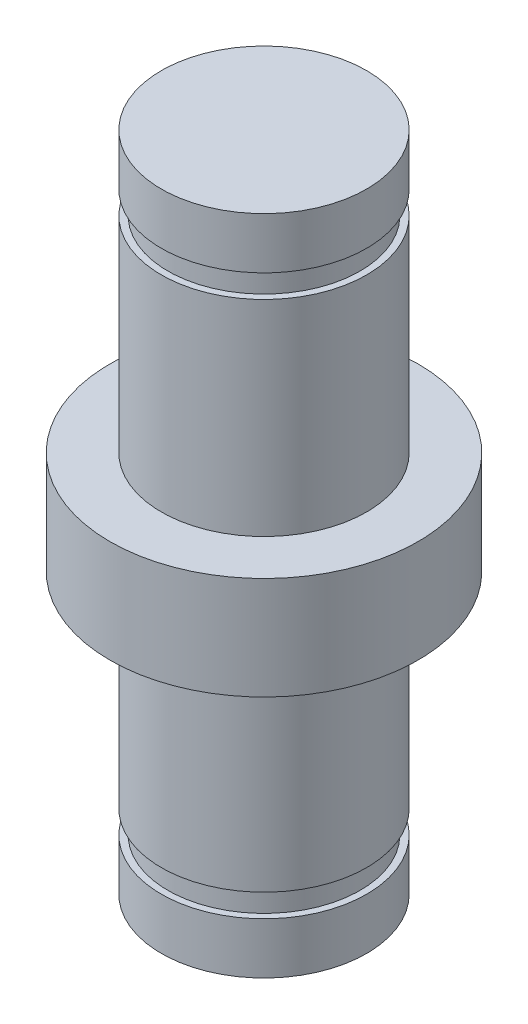
SolidWorks part; units mm, degrees
material "6061 Alloy"
ref_plane "Front Plane" through (0, 0, 0) normal (0, 0, 1) x (1, 0, 0)
ref_plane "Top Plane" through (0, 0, 0) normal (0, 1, 0) x (1, 0, 0)
ref_plane "Right Plane" through (0, 0, 0) normal (1, 0, 0) x (0, 0, -1)
sketch "Sketch1" plane through (0, 0, 0) normal (0, 0, 1) x (1, 0, 0)
  line L0 (0, 0) -> (0, 40.9448) construction
  line L1 (0, 40.9448) -> (6.35, 40.9448)
  line L2 (6.35, 40.9448) -> (6.35, 37.7698)
  line L3 (6.35, 0) -> (0, 0)
  line L4 (0, 0) -> (0, 40.9448) construction
  line L5 (6.35, 37.7698) -> (5.9436, 37.7698)
  line L6 (5.9436, 37.7698) -> (5.9436, 36.3474)
  line L7 (5.9436, 36.3474) -> (6.35, 36.3474)
  line L8 (6.35, 36.3474) -> (6.35, 23.6474)
  line L9 (6.35, 23.6474) -> (9.525, 23.6474)
  line L10 (9.525, 23.6474) -> (9.525, 17.2974)
  line L11 (9.525, 17.2974) -> (6.35, 17.2974)
  line L12 (6.35, 17.2974) -> (6.35, 4.5974)
  line L13 (6.35, 4.5974) -> (5.9436, 4.5974)
  line L14 (5.9436, 4.5974) -> (5.9436, 3.175)
  line L15 (5.9436, 3.175) -> (6.35, 3.175)
  line L16 (6.35, 3.175) -> (6.35, 0)
  line L17 (0, 0) -> (0, 40.9448)
  dimension "D1" = 12.7
  dimension "D2" = 1.4224
  dimension "D3" = 12.7
  dimension "D4" = 11.8872
  dimension "D5" = 3.175
  dimension "D6" = 6.35
  dimension "D7" = 19.05
revolve "Revolve1" add sketch "Sketch1" angle 360 about L17
